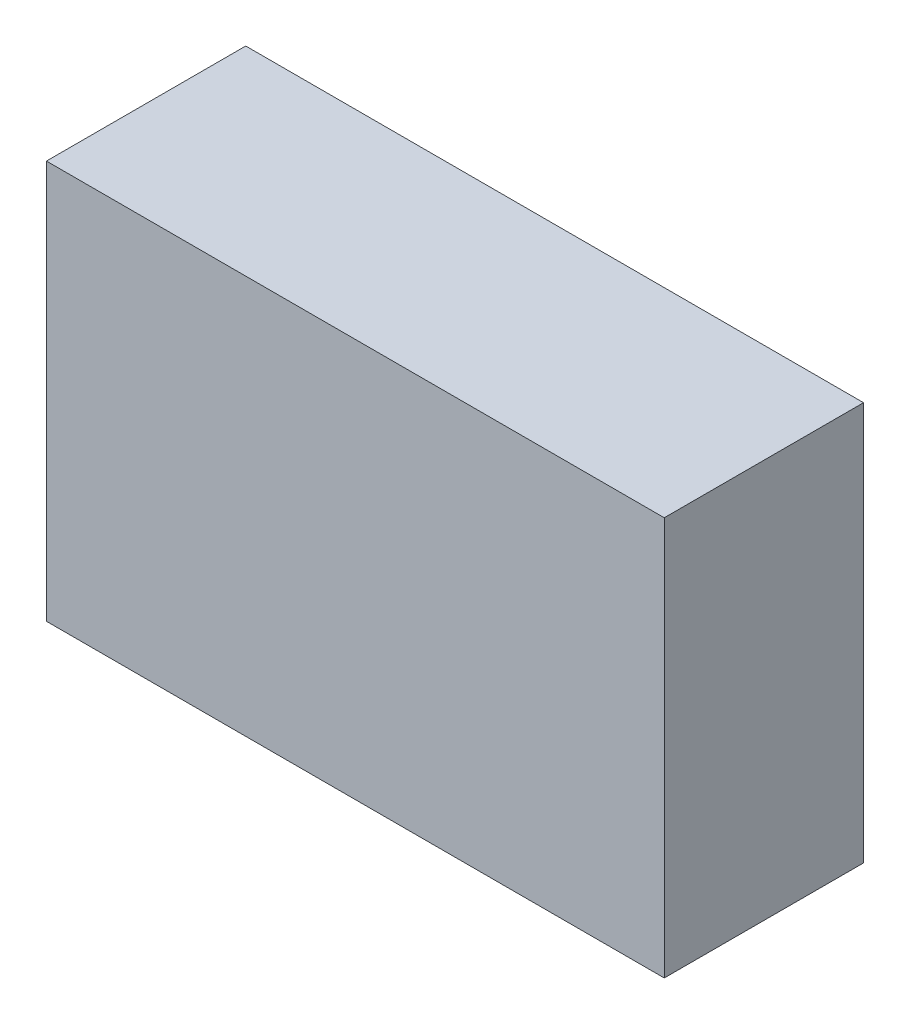
SolidWorks part; units mm, degrees
ref_plane "Front Plane" through (0, 0, 0) normal (0, 0, 1) x (1, 0, 0)
ref_plane "Top Plane" through (0, 0, 0) normal (0, 1, 0) x (1, 0, 0)
ref_plane "Right Plane" through (0, 0, 0) normal (1, 0, 0) x (0, 0, -1)
sketch "Sketch1" plane through (0, 0, 0) normal (0, 0, 1) x (1, 0, 0)
  line L1 (0, 0) -> (31, 0)
  line L2 (0, 0) -> (0, 20)
  line L3 (0, 20) -> (31, 20)
  line L4 (31, 0) -> (31, 20)
extrude "Boss-Extrude1" add sketch "Sketch1" against normal blind 10
